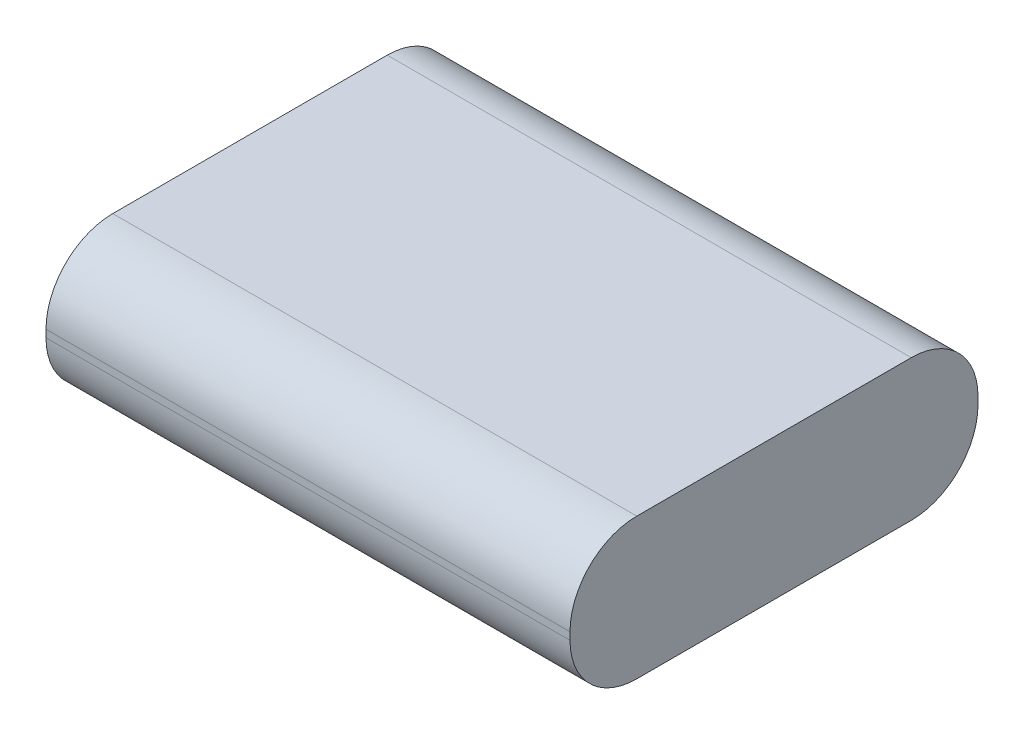
SolidWorks part; units mm, degrees
ref_plane "Front Plane" through (0, 0, 0) normal (0, 0, 1) x (1, 0, 0)
ref_plane "Top Plane" through (0, 0, 0) normal (0, 1, 0) x (1, 0, 0)
ref_plane "Right Plane" through (0, 0, 0) normal (1, 0, 0) x (0, 0, -1)
sketch "Sketch1" plane through (0, 0, 0) normal (0, 1, 0) x (1, 0, 0)
  line L1 (0, 0) -> (70.64, 0)
  line L2 (0, 0) -> (0, 55)
  line L3 (0, 55) -> (70.64, 55)
  line L4 (70.64, 0) -> (70.64, 55)
  dimension "D1" = 70.64
  dimension "D2" = 55
extrude "Boss-Extrude1" add sketch "Sketch1" along normal blind 19
fillet "Fillet2" radius 9 1 edges at (35.32, 19, -55)
fillet "Fillet3" radius 9 1 edges at (35.32, 0, -55)
fillet "Fillet4" radius 9 1 edges at (35.32, 19, 0)
fillet "Fillet5" radius 9 1 edges at (35.32, 0, 0)
